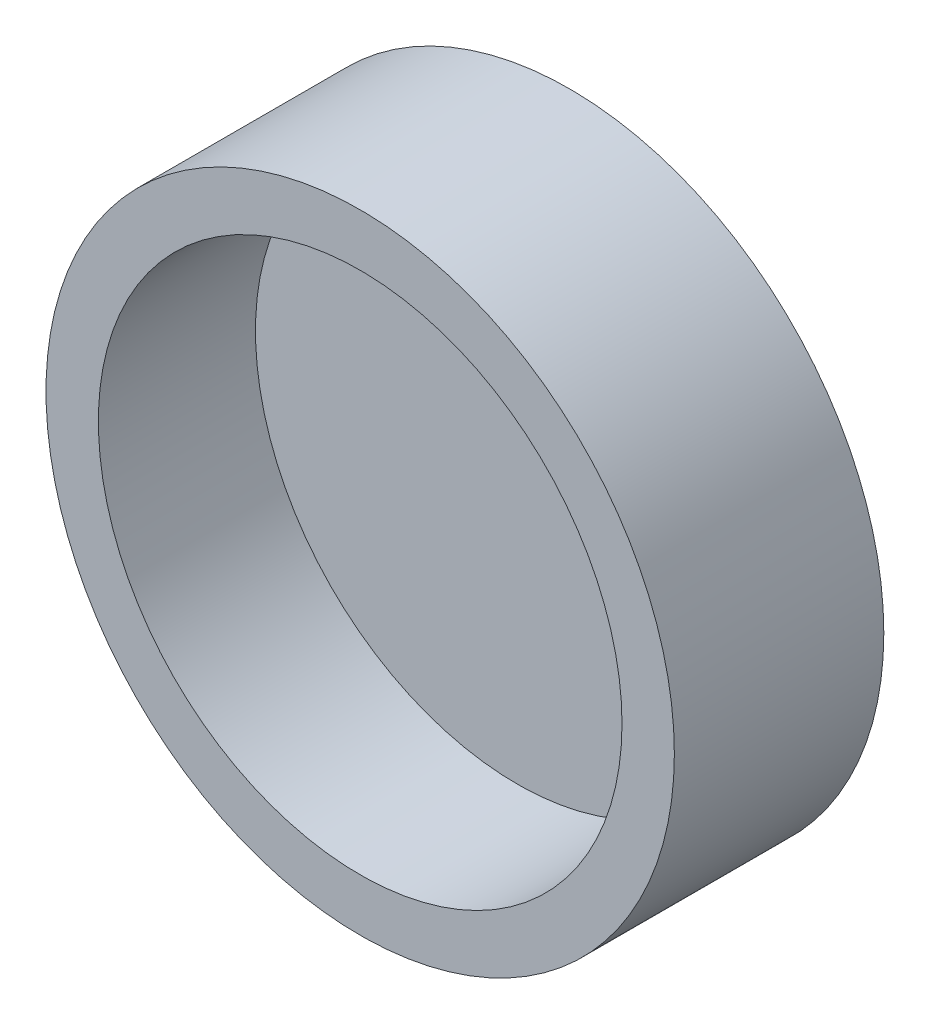
SolidWorks part; units mm, degrees
ref_plane "Ebene vorne" through (0, 0, 0) normal (0, 0, 1) x (1, 0, 0)
ref_plane "Ebene oben" through (0, 0, 0) normal (0, 1, 0) x (1, 0, 0)
ref_plane "Ebene rechts" through (0, 0, 0) normal (1, 0, 0) x (0, 0, -1)
sketch "Skizze1" plane through (0, 0, 0) normal (0, 0, 1) x (1, 0, 0)
  circle A0 centre (0, 0) radius 60
extrude "Aufsatz-Linear austragen1" add sketch "Skizze1" along normal blind 40
sketch "Skizze2" plane through (0, 0, 40) normal (0, 0, 1) x (1, 0, 0)
  circle A0 centre (0, 0) radius 50
extrude "Schnitt-Linear austragen1" cut sketch "Skizze2" against normal blind 30
